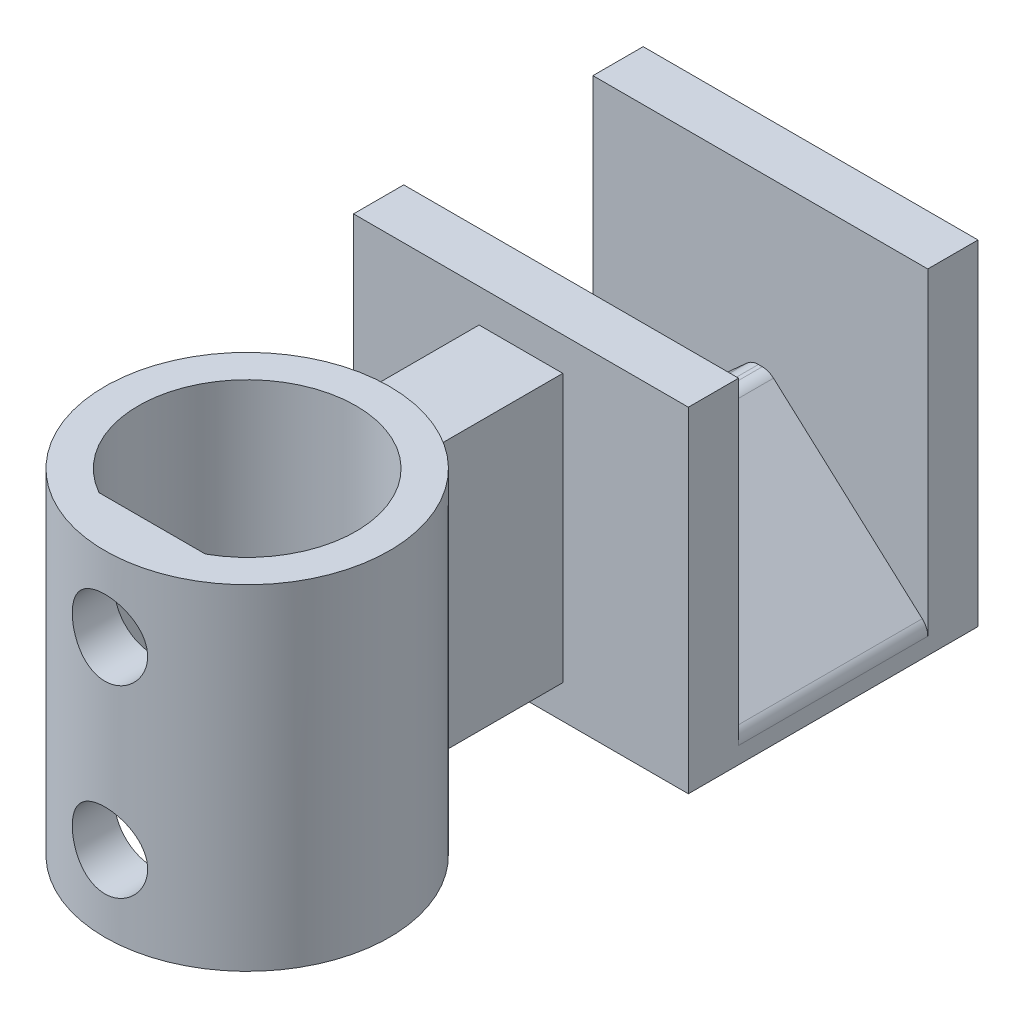
SolidWorks part; units mm, degrees
material "ABS"
ref_plane "Front Plane" through (0, 0, 0) normal (0, 0, 1) x (1, 0, 0)
ref_plane "Top Plane" through (0, 0, 0) normal (0, 1, 0) x (1, 0, 0)
ref_plane "Right Plane" through (0, 0, 0) normal (1, 0, 0) x (0, 0, -1)
sketch "Sketch2" plane through (0, 0, 0) normal (0, 0, 1) x (1, 0, 0)
  line L1 (-10, -5) -> (10, -5)
  line L2 (-10, -5) -> (-10, 5)
  line L3 (-10, 5) -> (10, 5)
  line L4 (10, -5) -> (10, 5)
  line L5 (-10, -5) -> (10, 5) construction
  line L6 (-10, 5) -> (10, -5) construction
  point P0 (0, 0)
  dimension "D1" = 10
  dimension "D2" = 20
extrude "Boss-Extrude1" add sketch "Sketch2" along normal mid plane 11.3
chamfer "Chamfer1" distance 9.5 angle 42 2 edges at (10, 5, 0) (-10, 5, 0)
fillet "Fillet3" radius 1 4 edges at (-10, -3.5538, 0) (10, -3.5538, 0) (0.5, 5, 0) (-0.5, 5, 0)
sketch "Sketch3" plane through (0, 0, 5.65) normal (0, 0, 1) x (1, 0, 0)
  line L0 (-10, -5) -> (10, -5) construction
  line L1 (-10, 15) -> (10, 15)
  line L2 (-10, 15) -> (-10, -5)
  line L3 (-10, -5) -> (10, -5)
  line L4 (10, 15) -> (10, -5)
  line L5 (-10, 15) -> (10, -5) construction
  line L6 (-10, -5) -> (10, 15) construction
  point P0 (0, 5)
  dimension "D1" = 20
  dimension "D2" = 20
extrude "Boss-Extrude2" add sketch "Sketch3" along normal blind 3
mirror "Mirror1" about plane through (0, 0, 0) normal (0, 0, 1) of "Boss-Extrude2"
sketch "Sketch6" plane through (0, 0, 0) normal (0, 1, 0) x (1, 0, 0)
  line L0 (3.175, -30.6718) -> (-3.175, -30.6718)
  arc A0 (3.175, -30.6718) -> (-3.175, -30.6718) centre (0, -25) ccw
  circle A1 centre (0, -25) radius 8.5
  dimension "D1" = 13
  dimension "D2" = 2
  dimension "D3" = 25
  dimension "D4" = 6.35
extrude "Boss-Extrude3" add sketch "Sketch6" along normal up to surface and the other way up to surface separate body up to face at (0, 15, 7.15) other way up to face at (0, -5, 0)
sketch "Sketch5" plane through (0, 0, 8.65) normal (0, 0, 1) x (1, 0, 0)
  line L0 (-10, -5) -> (10, -5) construction
  line L1 (-2.5, 13) -> (2.5, 13)
  line L2 (-2.5, 13) -> (-2.5, -3)
  line L3 (-2.5, -3) -> (2.5, -3)
  line L4 (2.5, 13) -> (2.5, -3)
  line L5 (-2.5, 13) -> (2.5, -3) construction
  line L6 (-2.5, -3) -> (2.5, 13) construction
  line L7 (10, 15) -> (-10, 15) construction
  point P0 (0, 5)
  dimension "D1" = 2
  dimension "D2" = 2
  dimension "D3" = 5
extrude "Boss-Extrude4" add sketch "Sketch5" along normal up to surface (8.226 mm away)
ref_plane "Plane1" through (0, 0, 20) normal (0, 0, 1) x (1, 0, 0)
sketch "Sketch7" plane through (0, 0, 20) normal (0, 0, 1) x (1, 0, 0)
  line L0 (-8.5, -5) -> (8.5, -5) construction
  line L1 (6.5, 15) -> (-6.5, 15) construction
  circle A0 centre (0, 10.5) radius 2.25
  circle A1 centre (0, -0.5) radius 2.25
  dimension "D1" = 4.5
  dimension "D2" = 4.5
  dimension "D3" = 4.5
  dimension "D4" = 4.5
extrude "Cut-Extrude1" cut sketch "Sketch7" along normal up to surface (13.1968 mm away)
